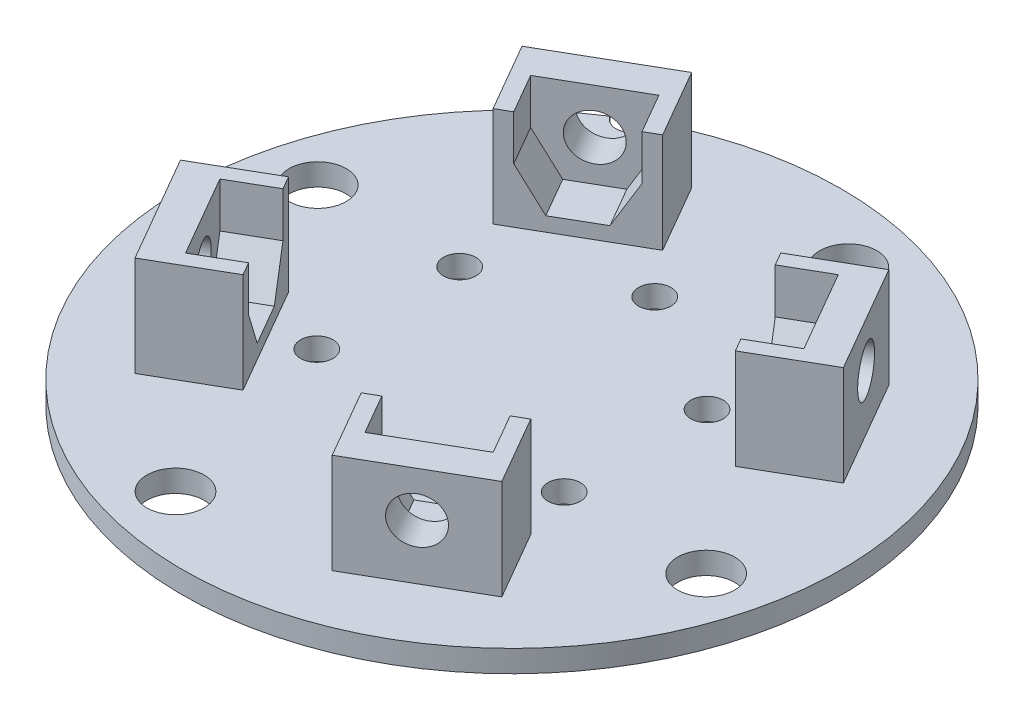
SolidWorks part; units mm, degrees
ref_plane "前视基准面" through (0, 0, 0) normal (0, 0, 1) x (1, 0, 0)
ref_plane "上视基准面" through (0, 0, 0) normal (0, 1, 0) x (1, 0, 0)
ref_plane "右视基准面" through (0, 0, 0) normal (1, 0, 0) x (0, 0, -1)
sketch "Sketch1" plane through (0, 0, 0) normal (0, 1, 0) x (1, 0, 0)
  line L0 (0, 13) -> (0, 0) construction
  line L1 (-11.2583, 6.5) -> (0, 13) construction
  line L2 (0, 0) -> (-24.1481, 6.4705) construction
  line L3 (-5.6292, 9.75) -> (0, 0) construction
  circle A0 centre (0, 13) radius 1.475
  circle A1 centre (11.2583, 6.5) radius 1.475
  circle A2 centre (11.2583, -6.5) radius 1.475
  circle A3 centre (0, -13) radius 1.475
  circle A4 centre (-11.2583, -6.5) radius 1.475
  circle A5 centre (-11.2583, 6.5) radius 1.475
  circle A6 centre (0, 0) radius 30
  circle A7 centre (-24.1481, 6.4705) radius 2.6
  circle A8 centre (6.4705, 24.1481) radius 2.6
  circle A9 centre (24.1481, -6.4705) radius 2.6
  circle A10 centre (-6.4705, -24.1481) radius 2.6
  point P16 (0, 0)
  point P27 (0, 0)
  dimension "D2" = 2.95
  dimension "D4" = 60
  dimension "D6" = 5.2
  dimension "D1" = 13
  dimension "D5" = 25
  dimension "D8" = 45
  dimension "D3" = 6
  dimension "D7" = 4
extrude "Boss-Extrude1" add sketch "Sketch1" along normal blind 2
sketch "Sketch2" plane through (0, 2, 0) normal (0, 1, 0) x (1, 0, 0)
  line L0 (0, 0) -> (-15, 25.9808)
  line L1 (0, 13) -> (-11.2583, 6.5)
  circle A0 centre (0, 0) radius 30 construction
  circle A1 centre (-15, 25.9808) radius 1.5
  circle M8 centre (0, 0) radius 30
  dimension "D1" = 3
extrude "Cut-Extrude1" cut sketch "Sketch2" against normal blind 10 contours L0 A1 M8 | A1 L0 M8 | A1 M8
sketch "Sketch8" plane through (0, 2, 0) normal (0, 1, 0) x (1, 0, 0)
  line L0 (-14.25, 24.6817) -> (0, 0)
  line L1 (-16.693, 17.6132) -> (-13.093, 11.3778)
  line L2 (-16.693, 17.6132) -> (-6.907, 23.2632)
  line L3 (-13.093, 11.3778) -> (-3.307, 17.0278)
  line L4 (-6.907, 23.2632) -> (-3.307, 17.0278)
  line L5 (-16.693, 17.6132) -> (-3.307, 17.0278) construction
  line L6 (-13.093, 11.3778) -> (-6.907, 23.2632) construction
  arc A0 (-16.2799, 25.1985) -> (-13.6826, 26.6981) centre (-15, 25.9808) ccw construction
  point P7 (-10, 17.3205)
  dimension "D1" = 20
  dimension "D2" = 11.3
  dimension "D3" = 7.2
extrude "Boss-Extrude3" add sketch "Sketch8" along normal blind 9.1 contours L4 L2 L0 L3 | L1 L3 L0 L2
pattern_circular "CirPattern1" count 4 every 90 about axis through (0, 0, 0) along (0, 1, 0) of "Boss-Extrude3"
sketch "Sketch9" plane through (-11.8, 0, -20.4382) normal (-0.5, 0, -0.866) x (-0.866, 0, 0.5)
  line L0 (0, 11.1) -> (0, 2)
  line L1 (5.65, 11.1) -> (-5.65, 11.1) construction
  line L2 (5.65, 2) -> (-5.65, 2) construction
  line L3 (-4.2724, 7) -> (-4.2724, 11.1)
  line L4 (2.1362, 10.7) -> (-2.1362, 10.7)
  line L5 (-2.1362, 10.7) -> (-4.2724, 7)
  line L6 (-4.2724, 7) -> (-2.1362, 3.3)
  line L7 (-2.1362, 3.3) -> (2.1362, 3.3)
  line L8 (2.1362, 3.3) -> (4.2724, 7)
  line L9 (4.2724, 7) -> (2.1362, 10.7)
  line L10 (-4.2724, 11.1) -> (4.2724, 11.1)
  line L11 (4.2724, 11.1) -> (4.2724, 7)
  circle A1 centre (0, 7) radius 3.7 construction
  line M11 (5.65, 11.1) -> (-5.65, 11.1)
  dimension "D1" = 7.4
  dimension "D2" = 5
extrude "Cut-Extrude2" cut sketch "Sketch9" against normal blind 5 from offset 3 contours L6 L7 L0 L4 L5 | L8 L9 L4 L0 L7 | L5 L4 L0 L3 M11 | L11 L0 L4 L9 M11 offset against normal yes
sketch "Sketch10" plane through (-11.8, 0, -20.4382) normal (-0.5, 0, -0.866) x (-0.866, 0, 0.5)
  line L0 (0, 11.1) -> (0, 2)
  line L1 (5.65, 11.1) -> (-5.65, 11.1) construction
  line L2 (5.65, 2) -> (-5.65, 2) construction
  line L3 (30, 2) -> (-30, 2) construction
  circle A0 centre (0, 7) radius 2.1
  dimension "D1" = 4.2
  dimension "D2" = 5
extrude "Cut-Extrude3" cut sketch "Sketch10" against normal blind 15 contours L0 A0 | L0 A0
pattern_circular "CirPattern2" count 4 every 90 about axis through (0, 0, 0) along (0, 1, 0) of "Cut-Extrude2"
pattern_circular "CirPattern3" count 4 every 90 about axis through (0, 2, 0) along (0, 1, 0) of "Cut-Extrude3"
